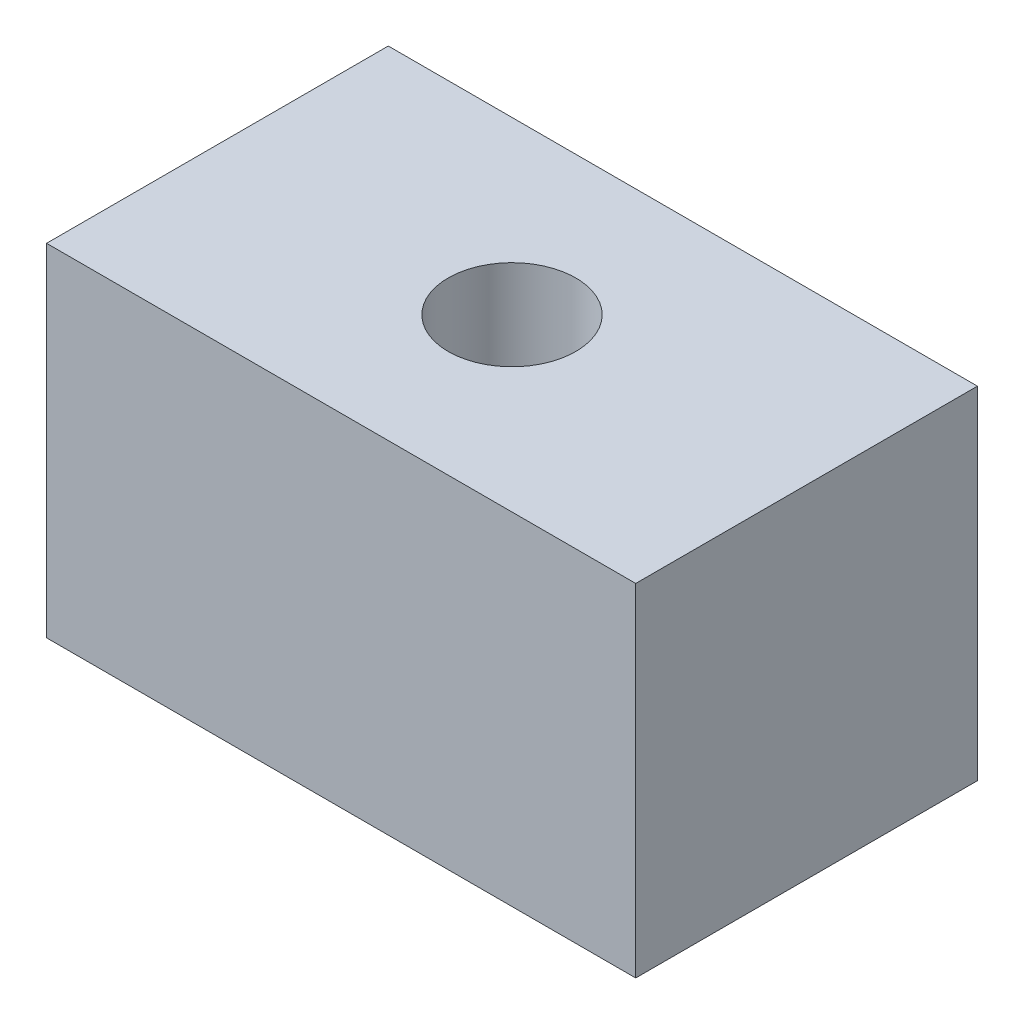
SolidWorks part; units mm, degrees
ref_plane "Front Plane" through (0, 0, 0) normal (0, 0, 1) x (1, 0, 0)
ref_plane "Top Plane" through (0, 0, 0) normal (0, 1, 0) x (1, 0, 0)
ref_plane "Right Plane" through (0, 0, 0) normal (1, 0, 0) x (0, 0, -1)
sketch "Sketch1" plane through (0, 0, 0) normal (1, 0, 0) x (0, 0, -1)
  line L1 (-7.366, 7.366) -> (7.366, 7.366)
  line L2 (-7.366, 7.366) -> (-7.366, -7.366)
  line L3 (-7.366, -7.366) -> (7.366, -7.366)
  line L4 (7.366, 7.366) -> (7.366, -7.366)
  line L5 (-7.366, 7.366) -> (7.366, -7.366) construction
  line L6 (-7.366, -7.366) -> (7.366, 7.366) construction
  point P0 (0, 0)
  dimension "D1" = 14.732
  dimension "D2" = 14.732
extrude "Boss-Extrude1" add sketch "Sketch1" along normal blind 25.4
sketch "Sketch2" plane through (0, 7.366, 0) normal (0, 1, 0) x (1, 0, 0)
  line L0 (0, 7.366) -> (0, -7.366) construction
  circle A0 centre (12.7, 0) radius 2.75
  point P6 (0, 0)
  dimension "D1" = 5.5
  dimension "D2" = 12.7
extrude "Cut-Extrude1" cut sketch "Sketch2" against normal through all
sketch "Sketch3" plane through (0, 0, -7.366) normal (0, 0, -1) x (-1, 0, 0)
  line L0 (0, -7.366) -> (0, 7.366) construction
  line L1 (0, 3.366) -> (-10, 3.366)
  line L2 (0, 3.366) -> (0, -3.492)
  line L3 (0, -3.492) -> (-10, -3.492)
  line L4 (-10, 3.366) -> (-10, -3.492)
  line L5 (-10, -0.063) -> (-4.92, -0.063) construction
  line L6 (-25.4, 7.366) -> (0, 7.366) construction
  circle A0 centre (-4.92, -0.063) radius 1.5875
  dimension "D2" = 3.175
  dimension "D1" = 6.858
  dimension "D3" = 5.08
  dimension "D4" = 10
  dimension "D5" = 4
extrude "Cut-Extrude2" cut sketch "Sketch3" against normal blind 1.778
fillet "Fillet1" radius 0.7937 2 edges at (10, 3.366, -6.477) (10, -3.492, -6.477)
sketch "Sketch5" plane through (0, 0, -7.366) normal (0, 0, -1) x (-1, 0, 0)
  line L0 (0, -7.366) -> (0, -3.492)
  line L1 (0, -7.366) -> (-3.9016, -7.366)
  line L2 (-25.4, -7.366) -> (0, -7.366) construction
sketch "Sketch6" plane through (0, 7.366, 0) normal (0, 1, 0) x (1, 0, 0)
  text T0 "Top"
